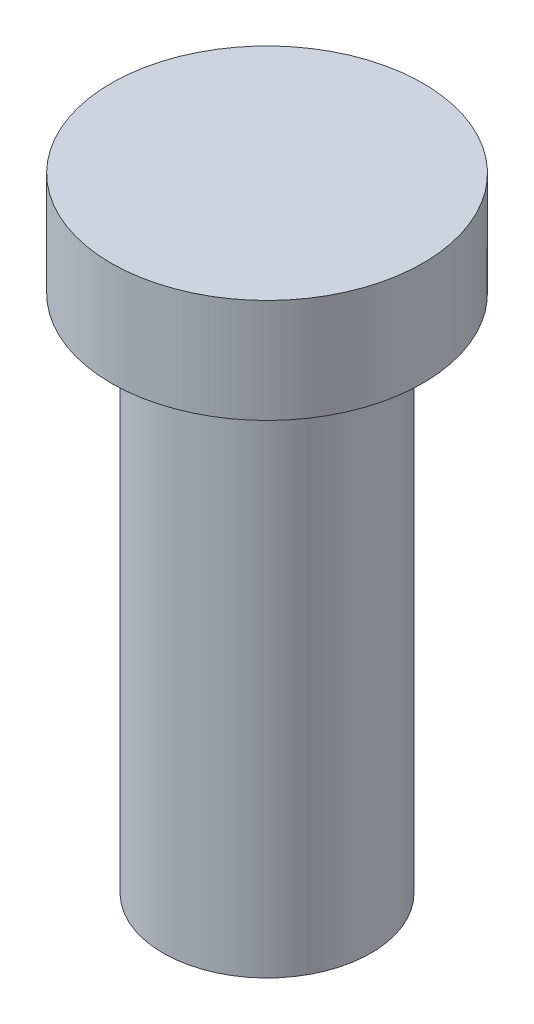
SolidWorks part; units mm, degrees
ref_plane "Plan de face" through (0, 0, 0) normal (0, 0, 1) x (1, 0, 0)
ref_plane "Plan de dessus" through (0, 0, 0) normal (0, 1, 0) x (1, 0, 0)
ref_plane "Plan de droite" through (0, 0, 0) normal (1, 0, 0) x (0, 0, -1)
sketch "Esquisse1" plane through (0, 0, 0) normal (0, 1, 0) x (1, 0, 0)
  circle A0 centre (0, 0) radius 2
  dimension "D1" = 4
extrude "Extrusion1" add sketch "Esquisse1" along normal blind 10
sketch "Esquisse2" plane through (0, 10, 0) normal (0, 1, 0) x (1, 0, 0)
  circle A0 centre (0, 0) radius 3
  dimension "D1" = 6
extrude "Extrusion2" add sketch "Esquisse2" along normal blind 2
